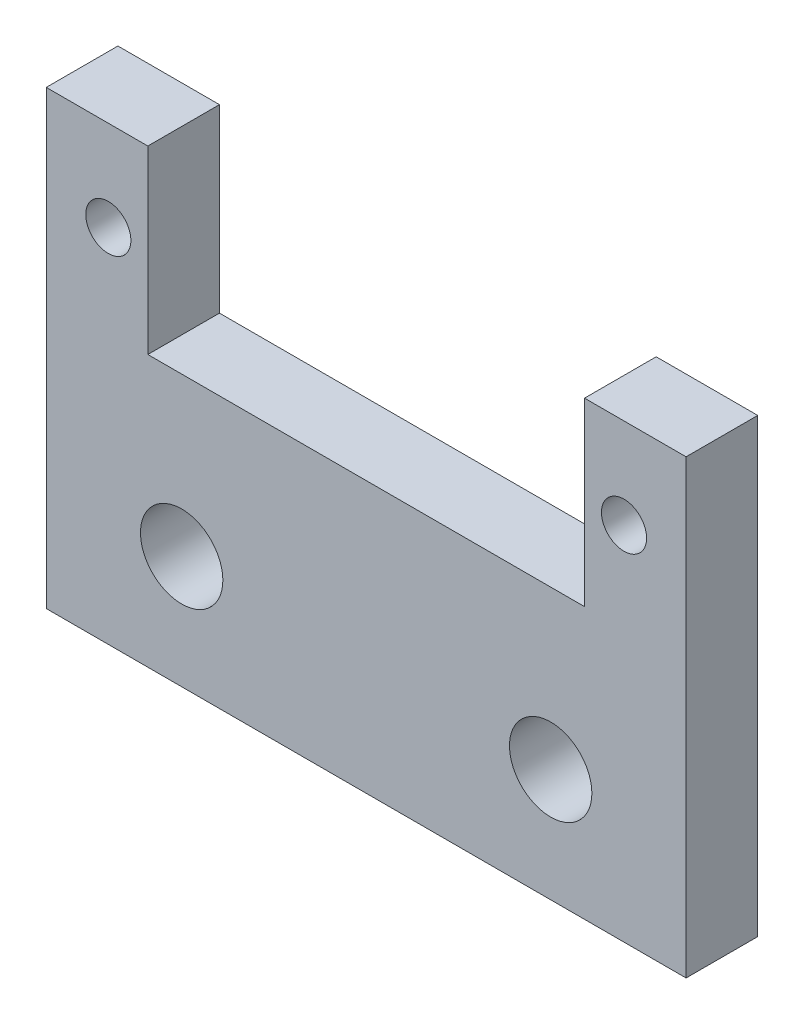
SolidWorks part; units mm, degrees
ref_plane "Front Plane" through (0, 0, 0) normal (0, 0, 1) x (1, 0, 0)
ref_plane "Top Plane" through (0, 0, 0) normal (0, 1, 0) x (1, 0, 0)
ref_plane "Right Plane" through (0, 0, 0) normal (1, 0, 0) x (0, 0, -1)
sketch "Sketch1" plane through (0, 0, 0) normal (0, 0, 1) x (1, 0, 0)
  line L0 (0, 8) -> (0, 0)
  line L1 (0, 8) -> (4.5, 8)
  line L2 (4.5, 8) -> (4.5, 0)
  line L3 (4.5, 0) -> (23.85, 0)
  line L4 (23.85, 0) -> (23.85, 8)
  line L5 (23.85, 8) -> (28.35, 8)
  line L6 (28.35, 8) -> (28.35, -12)
  line L7 (28.35, -12) -> (0, -12)
  line L8 (0, -12) -> (0, 0)
  line L12 (0, 4) -> (28.35, 4) construction
  circle A0 centre (2.75, 4) radius 1
  circle A1 centre (25.6, 4) radius 1
  circle A2 centre (6, -7) radius 1.825
  circle A3 centre (22.35, -7) radius 1.825
  dimension "D5" = 2
  dimension "D6" = 2
  dimension "D9" = 5
  dimension "D10" = 5
  dimension "D11" = 3.65
  dimension "D12" = 3.65
  dimension "D14" = 6
  dimension "D15" = 1.75
  dimension "D1" = 4.5
  dimension "D2" = 4.5
  dimension "D3" = 8
  dimension "D4" = 8
  dimension "D7" = 22.85
  dimension "D8" = 12
  dimension "D13" = 6
  dimension "D16" = 1.75
extrude "Boss-Extrude1" add sketch "Sketch1" along normal blind 3.175
